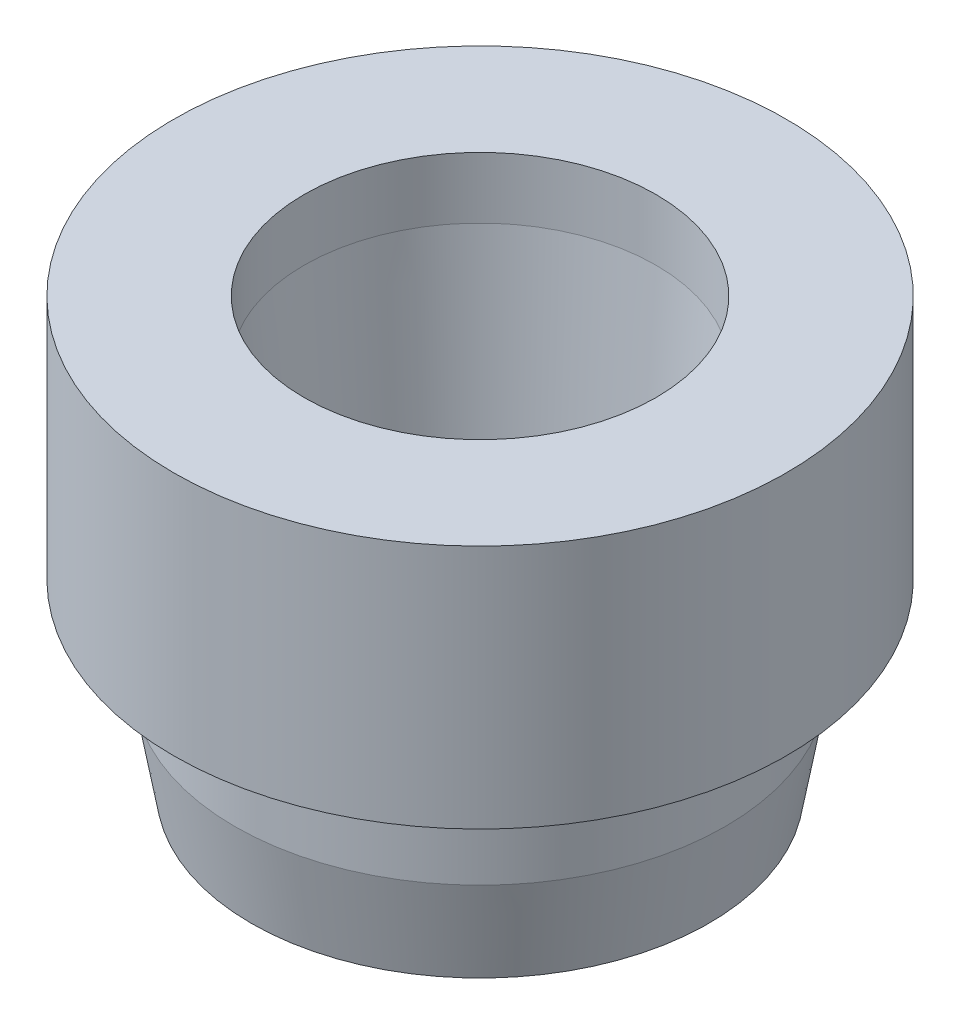
SolidWorks part; units mm, degrees
ref_plane "Płaszczyzna przednia" through (0, 0, 0) normal (0, 0, 1) x (1, 0, 0)
ref_plane "Płaszczyzna górna" through (0, 0, 0) normal (0, 1, 0) x (1, 0, 0)
ref_plane "Płaszczyzna prawa" through (0, 0, 0) normal (1, 0, 0) x (0, 0, -1)
sketch "Szkic1" plane through (0, 0, 0) normal (0, 0, 1) x (1, 0, 0)
  line L0 (0, 46.8801) -> (0, -36.8215) construction
  line L2 (-28.72, 46.8801) -> (-28.72, 36.8801)
  line L3 (-28.72, 36.8801) -> (-24.6971, -13.1199)
  line L4 (-28.72, 36.8801) -> (-28.72, -36.8215) construction
  line L5 (-24.6971, -13.1199) -> (-33.9936, -13.1199) construction
  line L6 (-24.6971, -13.1199) -> (-24.6971, -23.1199)
  line L7 (-24.6971, -23.1199) -> (-37.3551, -23.1199)
  line L8 (-50, 46.8801) -> (-50, 6.8801)
  line L9 (-28.72, 46.8801) -> (-50, 46.8801)
  line L10 (-50, 6.8801) -> (-40, 6.8801)
  line L11 (-40, 6.8801) -> (-40, -8.1199)
  line L12 (-40, -8.1199) -> (-37.3551, -23.1199)
  line L13 (-40, -8.1199) -> (-40, -29.3628) construction
  dimension "D1" = 4.6
  dimension "D2" = 50
  dimension "D3" = 10
  dimension "D4" = 28.72
  dimension "D5" = 50
  dimension "D6" = 40
  dimension "D7" = 10
revolve "Obrót1" add sketch "Szkic1" angle 360 about L0
